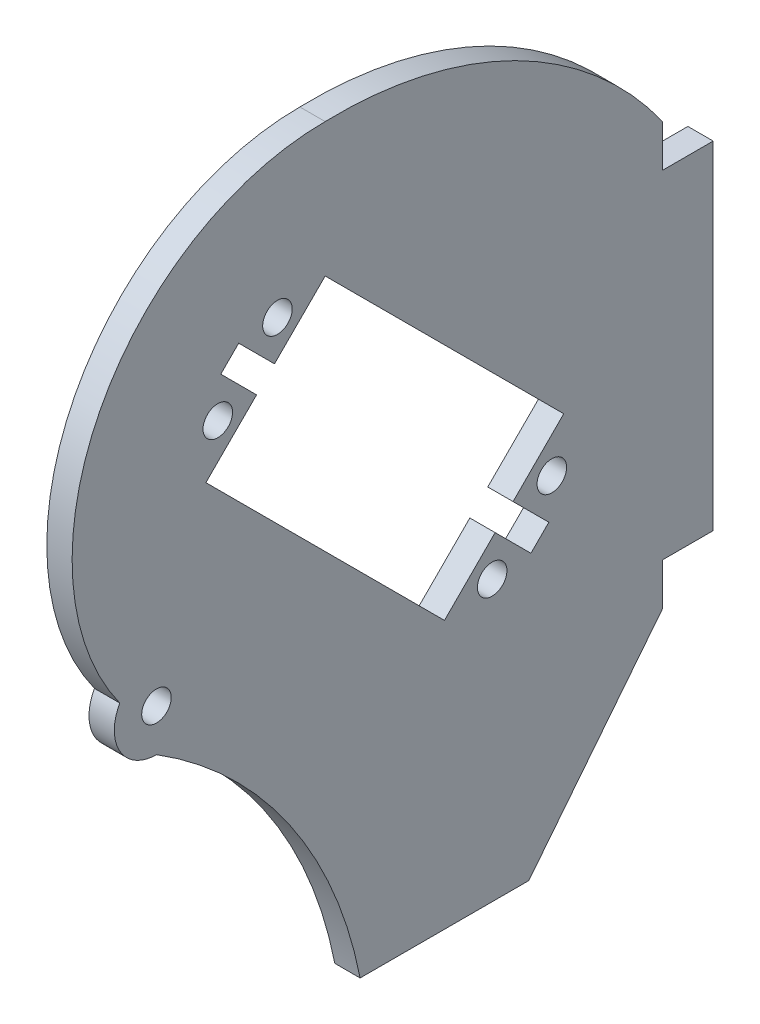
SolidWorks part; units mm, degrees
ref_plane "Alzado" through (0, 0, 0) normal (0, 0, 1) x (1, 0, 0)
ref_plane "Planta" through (0, 0, 0) normal (0, 1, 0) x (1, 0, 0)
ref_plane "Vista lateral" through (0, 0, 0) normal (1, 0, 0) x (0, 0, -1)
sketch "Croquis1" plane through (0, 0, 0) normal (1, 0, 0) x (0, 0, -1)
  line L0 (0, 0) -> (-7.0711, 7.0711) construction
  line L1 (-7.0711, 7.0711) -> (-14.1421, 0) construction
  line L2 (-14.1421, 0) -> (14.1421, -28.2843)
  line L3 (14.1421, -28.2843) -> (20.1507, -22.2757)
  line L4 (20.1507, -22.2757) -> (24.3934, -26.5183)
  line L5 (24.3934, -26.5183) -> (26.5165, -24.3952)
  line L6 (26.5165, -24.3952) -> (22.2739, -20.1525)
  line L7 (22.2739, -20.1525) -> (28.2843, -14.1421)
  line L8 (28.2843, -14.1421) -> (0, 14.1421)
  line L9 (0, 14.1421) -> (-6.0104, 8.1317)
  line L10 (-6.0104, 8.1317) -> (-10.253, 12.3744)
  line L11 (-10.253, 12.3744) -> (-12.3744, 10.253)
  line L12 (-12.3744, 10.253) -> (-8.1317, 6.0104)
  line L13 (-8.1317, 6.0104) -> (-14.1421, 0)
  line L14 (-10.253, 8.1317) -> (-12.7301, 5.6547) construction
  line L15 (-12.7301, 5.6547) -> (-10.6088, 3.5334) construction
  line L16 (-8.1317, 10.253) -> (-5.6585, 12.7263) construction
  line L17 (-5.6585, 12.7263) -> (-3.5372, 10.605) construction
  line L18 (24.3952, -22.2739) -> (26.8701, -19.799) construction
  line L19 (26.8701, -19.799) -> (24.7487, -17.6777) construction
  line L20 (22.272, -24.397) -> (19.7972, -26.8719) construction
  line L21 (19.7972, -26.8719) -> (17.6758, -24.7506) construction
  line L32 (14.1421, -60) -> (4.1421, -60) construction
  line L34 (40, -40) -> (40, -35) construction
  line L35 (14.1421, -60) -> (24.1421, -60) construction
  line L37 (4.1421, -60) -> (24.1421, -60)
  line L38 (24.1421, -60) -> (40, -40)
  line L39 (40, -40) -> (40, -35)
  line L40 (40, -35) -> (46, -35)
  line L41 (46, -35) -> (46, 5)
  line L42 (46, 5) -> (40, 5)
  line L43 (40, 10) -> (40, 5)
  circle A0 centre (-12.7301, 5.6547) radius 1.75
  circle A1 centre (-5.6585, 12.7263) radius 1.75
  circle A2 centre (26.8701, -19.799) radius 1.75
  circle A3 centre (19.7972, -26.8719) radius 1.75
  circle A4 centre (-20, -20) radius 1.75
  arc A5 (-20, -25) -> (4.1421, -60) centre (-48.212, -70.2863) cw
  arc A6 (-24.3465, -17.5285) -> (-20, -25) centre (-20, -20) ccw
  arc A10 (0, 30) -> (-24.3465, -17.5285) centre (0, 0) ccw
  arc A11 (40, 10) -> (0, 30) centre (1.2772, -17.4457) ccw
  dimension "D5" = 20
  dimension "D2" = 5
  dimension "D1" = 6
  dimension "D3" = 40
  dimension "D4" = 5
extrude "Saliente-Extruir1" add sketch "Croquis1" along normal blind 3
